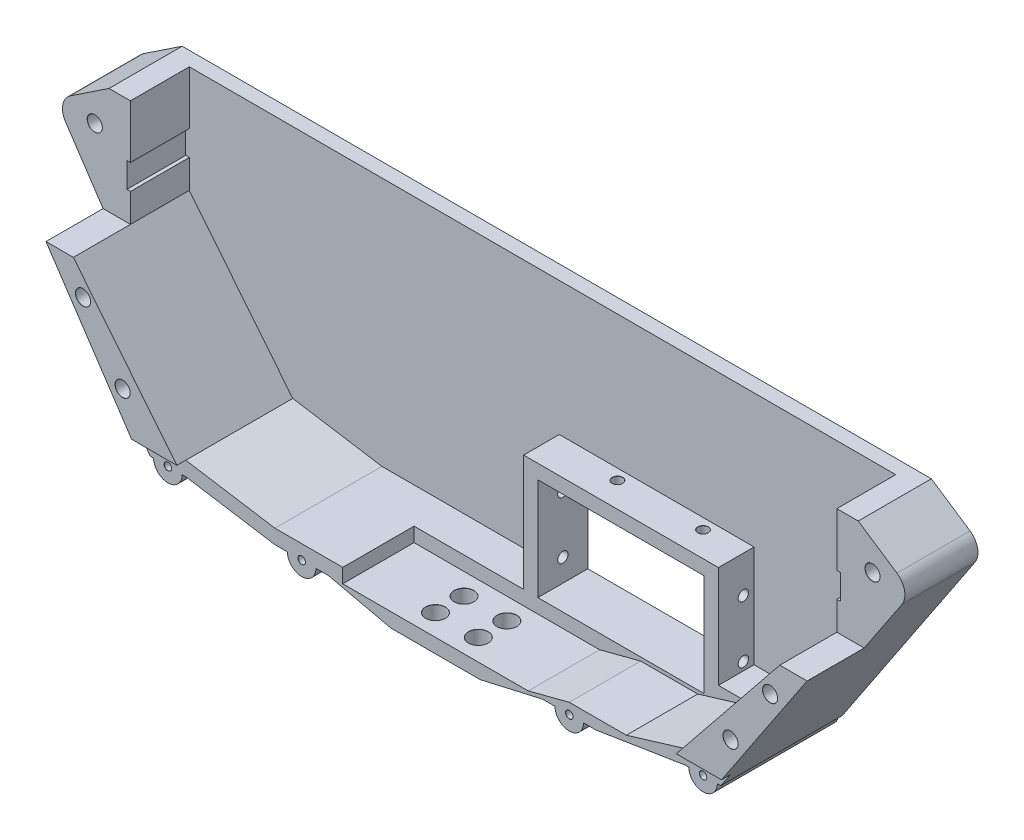
SolidWorks part; units mm, degrees
ref_plane "前视基准面" through (0, 0, 0) normal (0, 0, 1) x (1, 0, 0)
ref_plane "上视基准面" through (0, 0, 0) normal (0, 1, 0) x (1, 0, 0)
ref_plane "右视基准面" through (0, 0, 0) normal (1, 0, 0) x (0, 0, -1)
sketch "草图2" plane through (0, 0, 0) normal (0, 0, 1) x (1, 0, 0)
  line L0 (0, 0) -> (0, 68.1582) construction
  line L1 (80, 0) -> (-80, 0)
  line L2 (-80, 0) -> (-120, 60)
  line L3 (-120, 60) -> (-105, 70)
  line L4 (-105, 70) -> (105, 70)
  line L5 (120, 60) -> (105, 70)
  line L6 (80, 0) -> (120, 60)
  point P10 (0, 70)
  point P12 (0, 0)
  dimension "D1" = 210
  dimension "D2" = 70
  dimension "D3" = 15
  dimension "D4" = 60
  dimension "D5" = 40
extrude "凸台-拉伸1" add sketch "草图2" along normal blind 4
sketch "草图3" plane through (0, 0, 4) normal (0, 0, 1) x (1, 0, 0)
  line L0 (0, 70) -> (0, 0) construction
  line L1 (105, 70) -> (99, 70)
  line L3 (105, 70) -> (-105, 70) construction
  line L5 (-105, 70) -> (-120, 60) construction
  line L6 (-120, 60) -> (-105, 70)
  line L7 (-105, 70) -> (-99, 70)
  line L8 (-99, 70) -> (-99, 55)
  line L9 (-99, 55) -> (-100, 55)
  line L10 (-100, 55) -> (-100, 48)
  line L11 (-100, 48) -> (-99, 48)
  line L12 (-99, 48) -> (-99, 40)
  line L21 (99, 70) -> (99, 55)
  line L22 (99, 55) -> (100, 55)
  line L23 (100, 55) -> (100, 48)
  line L24 (100, 48) -> (99, 48)
  line L25 (99, 48) -> (99, 40)
  line L27 (120, 60) -> (105, 70) construction
  line L28 (120, 60) -> (105, 70)
  line L29 (-120, 60) -> (-80, 0) construction
  line L30 (-120, 60) -> (-106.6667, 40)
  line L31 (-106.6667, 40) -> (-99, 40)
  line L32 (120, 60) -> (106.6667, 40)
  line L33 (80, 0) -> (120, 60) construction
  line L34 (106.6667, 40) -> (99, 40)
  point P7 (-99, 62.5)
  dimension "D2" = 7
  dimension "D3" = 15
  dimension "D4" = 99
  dimension "D5" = 99
  dimension "D6" = 1
  dimension "D7" = 200
  dimension "D8" = 1
  dimension "D9" = 1
  dimension "D10" = 15
  dimension "D11" = 30
  dimension "D12" = 7
  dimension "D13" = 30
extrude "凸台-拉伸2" add sketch "草图3" along normal blind 16.5
sketch "草图4" plane through (0, 0, 4) normal (0, 0, 1) x (1, 0, 0)
  line L0 (20, 0) -> (20, 70) construction
  line L2 (-80, 0) -> (80, 0) construction
  line L3 (8.7, 28.6) -> (55.3, 28.6)
  line L4 (8.7, 28.6) -> (8.7, 0)
  line L5 (8.7, 0) -> (55.3, 0)
  line L6 (55.3, 28.6) -> (55.3, 0)
  dimension "D1" = 11.3
  dimension "D2" = 35.3
  dimension "D3" = 28.6
  dimension "D4" = 60
extrude "切除-拉伸1" cut sketch "草图4" against normal blind 4
sketch "草图5" plane through (0, 0, 4) normal (0, 0, 1) x (1, 0, 0)
  line L4 (55.3, 28.6) -> (55.3, 0)
  line L5 (55.3, 0) -> (80, 0)
  line L7 (4.7, 4) -> (-82.6667, 4)
  line L8 (-106.6667, 40) -> (-80, 0) construction
  line L9 (-82.6667, 4) -> (-80, 0)
  line L10 (-80, 0) -> (8.7, 0)
  line L13 (59.3, 4) -> (82.6667, 4)
  line L14 (80, 0) -> (106.6667, 40) construction
  line L15 (82.6667, 4) -> (80, 0)
  line L19 (4.7, 32.6) -> (59.3, 32.6)
  line L21 (4.7, 32.6) -> (4.7, 4)
  line L22 (59.3, 32.6) -> (59.3, 4)
  line L23 (55.3, 28.6) -> (8.7, 28.6) construction
  line L24 (8.7, 28.6) -> (8.7, 0)
  line L25 (8.7, 28.6) -> (55.3, 28.6)
  dimension "D1" = 4
  dimension "D2" = 4
  dimension "D3" = 4
  dimension "D4" = 4
  dimension "D5" = 4
extrude "凸台-拉伸3" add sketch "草图5" along normal blind 10
hole_wizard "M2.5 间隙孔1" positions "草图7" profile "草图8" hole size "M2.5" standard "ISO" end condition through all
sketch "草图7" plane through (0, 32.6, 0) normal (0, 1, 0) x (1, 0, 0)
  line L1 (4.7, -14) -> (4.7, -4) construction
  line L2 (99, -4) -> (-99, -4) construction
  line L3 (59.3, -4) -> (4.7, -4) construction
  point P0 (24, -7)
  point P2 (48, -7)
  dimension "D1" = 19.3
  dimension "D2" = 24
  dimension "D3" = 3
  dimension "D4" = 3
sketch "草图8" plane through (24, 32.6, 7) normal (1, 0, 0) x (0, 0, 1)
  line L0 (0, 0) -> (0, 32.6)
  line L1 (0, 32.6) -> (1.45, 32.6)
  line L2 (1.45, 32.6) -> (1.45, 0.025)
  line L3 (1.45, 0.025) -> (1.475, 0)
  line L5 (1.475, 0) -> (0, 0)
  line L6 (-1.45, 0.025) -> (-1.475, 0) construction
  line L11 (0, -6.35) -> (0, 107.95) construction
  dimension "通孔孔直径" = 2.9
  dimension "通孔孔深度" = 32.6
  dimension "近端锥形沉头孔直径" = 2.95
  dimension "近端锥形沉头孔角度" = 90
hole_wizard "M2.5 间隙孔2" positions "草图11" profile "草图12" hole size "M2.5" standard "ISO" end condition through all
sketch "草图11" plane through (4.7, 0, 0) normal (-1, 0, 0) x (0, 0, 1)
  line L0 (14, 32.6) -> (4, 32.6) construction
  line L1 (4, 32.6) -> (4, 4) construction
  point P0 (7, 22.3)
  point P2 (7, 6.3)
  dimension "D1" = 10.3
  dimension "D2" = 16
  dimension "D3" = 3
  dimension "D4" = 3
sketch "草图12" plane through (4.7, 22.3, 7) normal (0, 1, 0) x (0, 0, 1)
  line L0 (0, 0) -> (0, 115.3)
  line L1 (0, 115.3) -> (1.45, 115.3)
  line L2 (1.45, 115.3) -> (1.45, 0.025)
  line L3 (1.45, 0.025) -> (1.475, 0)
  line L5 (1.475, 0) -> (0, 0)
  line L6 (-1.45, 0.025) -> (-1.475, 0) construction
  line L11 (0, -6.35) -> (0, 107.95) construction
  dimension "通孔孔直径" = 2.9
  dimension "通孔孔深度" = 115.3
  dimension "近端锥形沉头孔直径" = 2.95
  dimension "近端锥形沉头孔角度" = 90
hole_wizard "M5 螺纹孔的螺纹孔钻头1" positions "草图15" profile "草图14" hole size "M5" standard "ISO"
sketch "草图15" plane through (0, 0, 20.5) normal (0, 0, 1) x (1, 0, 0)
  line L0 (0, 0) -> (0, 70) construction
  line L3 (-99, 70) -> (-105, 70) construction
  line L5 (-99, 55) -> (-99, 70) construction
  point P0 (-109, 59.5)
  point P22 (109, 59.5)
  dimension "D1" = 10.5
  dimension "D2" = 10
sketch "草图14" plane through (-109, 59.5, 20.5) normal (1, 0, 0) x (0, -1, 0)
  line L0 (0, 0) -> (0, 6.2618)
  line L1 (0, 6.2618) -> (2.1, 5)
  line L2 (2.1, 5) -> (2.1, 0.025)
  line L3 (2.1, 0.025) -> (2.125, 0)
  line L5 (2.125, 0) -> (0, 0)
  line L6 (-2.1, 0.025) -> (-2.125, 0) construction
  line L10 (0, 6.2618) -> (-2.1, 5) construction
  line L11 (0, -6.35) -> (0, 107.95) construction
  dimension "孔直径" = 4.2
  dimension "孔深度" = 5
  dimension "近端锥形沉头孔直径" = 4.25
  dimension "近端锥形沉头孔角度" = 90
  dimension "导头角度" = 118
sketch "草图16" plane through (0, 0, 0) normal (0, 0, -1) x (-1, 0, 0)
  line L0 (0, 2.9147) -> (0, 95.9423) construction
  line L1 (-70, 0) -> (-45, -4)
  line L2 (-55.3, 0) -> (-80, 0) construction
  line L3 (-45, -4) -> (45, -4)
  line L5 (70, 0) -> (45, -4)
  line L6 (-70, 0) -> (70, 0)
  point P9 (0, -4)
  point P14 (0, 0)
  dimension "D1" = 140
  dimension "D2" = 45
  dimension "D3" = 70
  dimension "D4" = 4
extrude "凸台-拉伸4" add sketch "草图16" against normal blind 17
sketch "草图17" plane through (0, 0, 17) normal (0, 0, 1) x (1, 0, 0)
  line L0 (0, 0) -> (0, 19.9591) construction
  line L2 (-30, -4) -> (-12.5, -8)
  line L3 (45, -4) -> (-45, -4) construction
  line L4 (-12.5, -8) -> (12.5, -8)
  line L5 (-30, -4) -> (30, -4)
  line L7 (30, -4) -> (12.5, -8)
  point P9 (0, -8)
  point P13 (0, -4)
  dimension "D1" = 4
  dimension "D2" = 30
  dimension "D3" = 25
extrude "凸台-拉伸5" add sketch "草图17" along normal blind 34 from offset 17 offset against normal yes
sketch "草图19" plane through (0, 0, 14) normal (0, 0, 1) x (1, 0, 0)
  line L0 (-78.6667, 4) -> (-82.6667, 4)
  line L1 (4.7, 4) -> (-82.6667, 4) construction
  line L2 (-82.6667, 4) -> (-80, 0)
  line L3 (-80, 0) -> (-70, 0)
  line L4 (-70, 0) -> (-45, -4)
  line L5 (-45, -4) -> (-26, -4)
  line L6 (30, -4) -> (-30, -4) construction
  line L9 (0, 0) -> (0, 21.1489) construction
  line L10 (-78.6667, 4) -> (-70, 4)
  line L19 (4.7, 4) -> (-82.6667, 4) construction
  line L20 (-70, 4) -> (-45, 0)
  line L21 (-70, 0) -> (70, 0) construction
  line L22 (-45, 0) -> (-26, 0)
  line L23 (-26, 0) -> (-26, -4)
  line L24 (45, 0) -> (26, 0)
  line L25 (70, 4) -> (45, 0)
  line L26 (78.6667, 4) -> (70, 4)
  line L27 (78.6667, 4) -> (82.6667, 4)
  line L28 (82.6667, 4) -> (80, 0)
  line L29 (80, 0) -> (70, 0)
  line L30 (70, 0) -> (45, -4)
  line L31 (45, -4) -> (26, -4)
  line L32 (26, 0) -> (26, -4)
  dimension "D1" = 4
  dimension "D2" = 4
extrude "凸台-拉伸6" add sketch "草图19" along normal up to surface (20 mm away) up to face at (0, -6, 34)
sketch "草图20" plane through (0, 0, 17) normal (0, 0, 1) x (1, 0, 0)
  line L4 (26, 0) -> (-26, 0)
  line L5 (-26, 0) -> (-26, -4)
  line L6 (-26, -4) -> (26, -4)
  line L7 (26, -4) -> (26, 0)
  line L8 (26, 0) -> (-26, 0)
  line L9 (-26, 0) -> (-26, -4)
  line L10 (-26, -4) -> (26, -4)
  line L11 (26, -4) -> (26, 0)
  dimension "D1" = 0
extrude "切除-拉伸2" cut sketch "草图20" against normal up to surface (3 mm away) up to face at (19.1818, 12.7316, 14)
sketch "草图21" plane through (0, 0, 14) normal (0, 0, 1) x (1, 0, 0)
  line L0 (4.7, 4) -> (4.7, 0)
  line L1 (4.7, 0) -> (-45, 0)
  line L2 (-45, 0) -> (-70, 4)
  line L3 (-70, 4) -> (4.7, 4)
extrude "切除-拉伸3" cut sketch "草图21" against normal up to surface (10 mm away) up to face at (6.4, 39.66, 4)
sketch "草图22" plane through (0, 0, 34) normal (0, 0, 1) x (1, 0, 0)
  line L0 (-70, 0) -> (-80, 0) construction
  line L1 (-30, -4) -> (-45, -4) construction
  line L2 (45, -4) -> (30, -4) construction
  line L3 (80, 0) -> (70, 0) construction
  circle A0 centre (-75, 0) radius 4
  circle A1 centre (-37.5, -4) radius 4
  circle A2 centre (37.5, -4) radius 4
  circle A3 centre (75, 0) radius 4
extrude "凸台-拉伸7" add sketch "草图22" against normal up to surface (34 mm away) up to face at (32, 14.3, 0)
hole_wizard "M2.5 螺纹孔的螺纹孔钻头1" positions "草图23" profile "草图24" hole size "M2.5" standard "ISO"
sketch "草图23" plane through (0, 0, 34) normal (0, 0, 1) x (1, 0, 0)
  point P0 (-75, 0)
  point P3 (-37.5, -4)
  point P6 (37.5, -4)
  point P9 (75, 0)
sketch "草图24" plane through (-75, 0, 34) normal (1, 0, 0) x (0, -1, 0)
  line L0 (0, 0) -> (0, 10.6159)
  line L1 (0, 10.6159) -> (1.025, 10)
  line L2 (1.025, 10) -> (1.025, 0.025)
  line L3 (1.025, 0.025) -> (1.05, 0)
  line L5 (1.05, 0) -> (0, 0)
  line L6 (-1.025, 0.025) -> (-1.05, 0) construction
  line L10 (0, 10.6159) -> (-1.025, 10) construction
  line L11 (0, -6.35) -> (0, 107.95) construction
  dimension "孔直径" = 2.05
  dimension "孔深度" = 10
  dimension "近端锥形沉头孔直径" = 2.1
  dimension "近端锥形沉头孔角度" = 90
  dimension "导头角度" = 118
sketch "草图25" plane through (0, 0, 34) normal (0, 0, 1) x (1, 0, 0)
  line L2 (26, 0) -> (26, -4)
  line L6 (53.4995, -1) -> (70, 4)
  line L7 (70, 4) -> (45, 0)
  line L8 (45, 0) -> (26, 0)
  line L11 (26, -4) -> (37.5152, -1)
  line L12 (37.5152, -1) -> (53.4995, -1)
  circle A0 centre (37.5, -4) radius 1.025 construction
  dimension "D1" = 3
extrude "切除-拉伸4" cut sketch "草图25" against normal up to surface (20 mm away) up to face at (25.0769, 9.5422, 14)
sketch "草图26" plane through (0, 0, 4) normal (0, 0, 1) x (1, 0, 0)
  line L0 (0, 0) -> (0, 77.0126) construction
  line L3 (-99, 40) -> (-106.6667, 40)
  line L4 (-106.6667, 40) -> (-82.6667, 4)
  line L5 (-82.6667, 4) -> (-70, 4)
  line L6 (-70, 4) -> (-99, 40)
  line L7 (82.6667, 4) -> (70, 4)
  line L8 (106.6667, 40) -> (82.6667, 4)
  line L9 (99, 40) -> (106.6667, 40)
  line L10 (70, 4) -> (99, 40)
extrude "凸台-拉伸8" add sketch "草图26" along normal blind 32.5
hole_wizard "M5 螺纹孔的螺纹孔钻头2" positions "草图29" profile "草图28" hole size "M5" standard "ISO"
sketch "草图29" plane through (0, 0, 36.5) normal (0, 0, 1) x (1, 0, 0)
  line L0 (-106.6667, 40) -> (-82.6667, 4) construction
  line L1 (-79, 0) -> (-80, 0) construction
  line L2 (0, 0) -> (0, 73.4984) construction
  point P0 (-96.2866, 31.641)
  point P2 (-85.1926, 15)
  point P18 (85.1926, 15)
  point P19 (96.2866, 31.641)
  dimension "D1" = 4
  dimension "D2" = 4
  dimension "D3" = 20
  dimension "D4" = 15
sketch "草图28" plane through (-96.2866, 31.641, 36.5) normal (1, 0, 0) x (0, -1, 0)
  line L0 (0, 0) -> (0, 11.2618)
  line L1 (0, 11.2618) -> (2.1, 10)
  line L2 (2.1, 10) -> (2.1, 0.025)
  line L3 (2.1, 0.025) -> (2.125, 0)
  line L5 (2.125, 0) -> (0, 0)
  line L6 (-2.1, 0.025) -> (-2.125, 0) construction
  line L10 (0, 11.2618) -> (-2.1, 10) construction
  line L11 (0, -6.35) -> (0, 107.95) construction
  dimension "孔直径" = 4.2
  dimension "孔深度" = 10
  dimension "近端锥形沉头孔直径" = 4.25
  dimension "近端锥形沉头孔角度" = 90
  dimension "导头角度" = 118
fillet "圆角1" radius 5 2 edges at (120, 60, 10.25) (-120, 60, 10.25)
hole_wizard "M5 间隙孔1" positions "草图31" profile "草图32" hole size "M5" standard "ISO"
sketch "草图31" plane through (0, -4, 0) normal (0, 1, 0) x (1, 0, 0)
  line L0 (-26, -34) -> (-26, -14) construction
  line L1 (26, -34) -> (26, -14) construction
  line L2 (105, 0) -> (-105, 0) construction
  point P0 (-6, -20)
  point P2 (6, -20)
  point P4 (6, -28)
  point P6 (-6, -28)
  dimension "D1" = 20
  dimension "D2" = 20
  dimension "D3" = 20
  dimension "D4" = 20
  dimension "D5" = 20
  dimension "D6" = 20
  dimension "D7" = 8
  dimension "D8" = 8
sketch "草图32" plane through (-6, -4, 20) normal (1, 0, 0) x (0, 0, 1)
  line L0 (0, 0) -> (0, 11.6524)
  line L1 (0, 11.6524) -> (2.75, 10)
  line L2 (2.75, 10) -> (2.75, 0.025)
  line L3 (2.75, 0.025) -> (2.775, 0)
  line L5 (2.775, 0) -> (0, 0)
  line L6 (-2.75, 0.025) -> (-2.775, 0) construction
  line L10 (0, 11.6524) -> (-2.75, 10) construction
  line L11 (0, -6.35) -> (0, 107.95) construction
  dimension "孔直径" = 5.5
  dimension "孔深度" = 10
  dimension "近端锥形沉头孔直径" = 5.55
  dimension "近端锥形沉头孔角度" = 90
  dimension "导头角度" = 118
